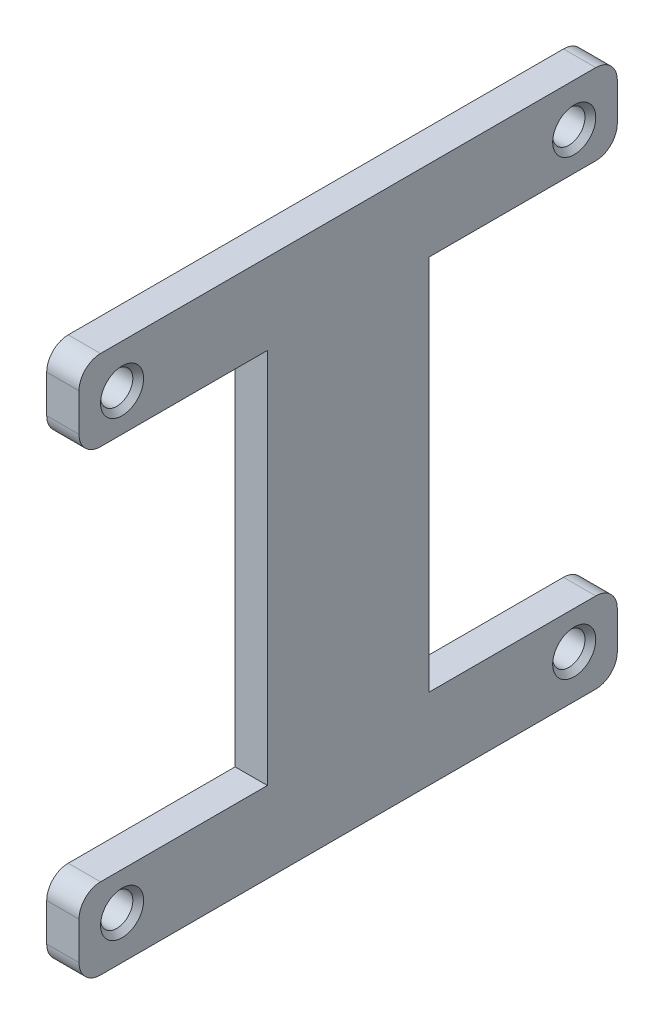
SolidWorks part; units mm, degrees
ref_plane "前视基准面" through (0, 0, 0) normal (0, 0, 1) x (1, 0, 0)
ref_plane "上视基准面" through (0, 0, 0) normal (0, 1, 0) x (1, 0, 0)
ref_plane "右视基准面" through (0, 0, 0) normal (1, 0, 0) x (0, 0, -1)
sketch "草图1" plane through (0, 0, 0) normal (1, 0, 0) x (0, 0, -1)
  line L0 (0, 0) -> (0, 29071.4302) construction
  line L1 (25, 25) -> (-25, 25)
  line L2 (-25, 25) -> (-25, 17.5)
  line L3 (-25, 17.5) -> (-7.5, 17.5)
  line L4 (-7.5, 17.5) -> (-7.5, -17.5)
  line L5 (0, 0) -> (-29071.4302, 0) construction
  line L6 (7.5, 17.5) -> (7.5, -17.5)
  line L7 (25, 17.5) -> (7.5, 17.5)
  line L8 (25, 25) -> (25, 17.5)
  line L9 (0, 0) -> (0, -29071.4302) construction
  line L10 (25, -25) -> (25, -17.5)
  line L11 (25, -17.5) -> (7.5, -17.5)
  line L12 (-25, -17.5) -> (-7.5, -17.5)
  line L13 (-25, -25) -> (-25, -17.5)
  line L14 (25, -25) -> (-25, -25)
  point P13 (0, 25)
  point P19 (7.5, 0)
  point P20 (-7.5, 0)
  point P22 (0, -25)
  dimension "D1" = 35
  dimension "D2" = 17.5
  dimension "D3" = 15
  dimension "D4" = 50
  dimension "D5" = 50
extrude "凸台-拉伸1" add sketch "草图1" along normal blind 3
sketch "草图2" plane through (3, 0, 0) normal (1, 0, 0) x (0, 0, -1)
  line L0 (0, 0) -> (0, 50000) construction
  line L1 (-25, 17.5) -> (-7.5, 17.5) construction
  circle A0 centre (-21, 21) radius 1.5
  circle A1 centre (-21, -21) radius 1.5
  circle A2 centre (21, -21) radius 1.5
  circle A3 centre (21, 21) radius 1.5
  point P7 (-21.247, 20.6827)
  point P14 (0, 0)
  dimension "D1" = 3
  dimension "D2" = 3
  dimension "D3" = 42
  dimension "D4" = 3.5
  dimension "D5" = 42
extrude "切除-拉伸1" cut sketch "草图2" against normal blind 3
chamfer "倒角1" distance 0.5 angle 45 4 edges at (3, -21, 19.5) (3, -21, -19.5) (3, 21, -19.5) (3, 21, 19.5)
fillet "圆角1" radius 2 8 edges at (1.5, -17.5, 25) (1.5, -25, 25) (1.5, -25, -25) (1.5, -17.5, -25) (1.5, 17.5, -25) (1.5, 25, -25) (1.5, 17.5, 25) (1.5, 25, 25)
